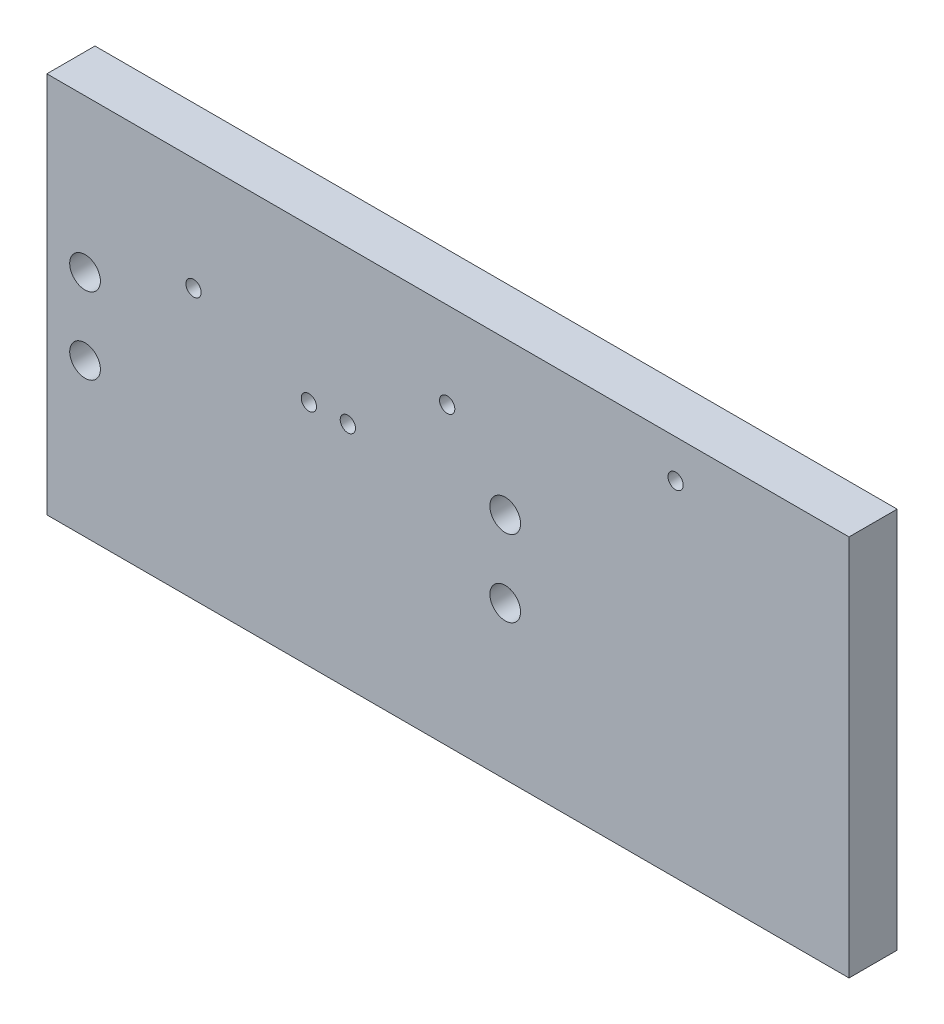
SolidWorks part; units mm, degrees
ref_plane "Front Plane" through (0, 0, 0) normal (0, 0, 1) x (1, 0, 0)
ref_plane "Top Plane" through (0, 0, 0) normal (0, 1, 0) x (1, 0, 0)
ref_plane "Right Plane" through (0, 0, 0) normal (1, 0, 0) x (0, 0, -1)
ref_plane "Dielectric_Layer Layer 1" through (0, 0, 1.6) normal (0, 0, 1) x (1, 0, 0)
sketch "Sketch1" plane through (0, 0, 0) normal (0, 0, 1) x (1, 0, 0)
  line L0 (0, 0) -> (26.67, 0)
  line L1 (26.67, 0) -> (26.67, 12.7)
  line L2 (26.67, 12.7) -> (0, 12.7)
  line L3 (0, 12.7) -> (0, 0)
extrude "Board_Outline" add sketch "Sketch1" along normal blind 1.6 separate body
sketch "Sketch2" plane through (0, 0, 0) normal (0, 0, 1) x (1, 0, 0)
  circle A0 centre (8.7122, 7.5946) radius 0.254
  circle A1 centre (10.0076, 7.62) radius 0.254
  circle A2 centre (13.3096, 9.8298) radius 0.254
  circle A3 centre (20.9042, 11.43) radius 0.254
  circle A4 centre (4.8768, 8.9662) radius 0.254
extrude "NPTH" cut sketch "Sketch2" along normal through all
sketch "Sketch3" plane through (0, 0, 0) normal (0, 0, 1) x (1, 0, 0)
  circle A0 centre (1.27, 7.62) radius 0.51
  circle A1 centre (1.27, 5.08) radius 0.51
  circle A2 centre (15.24, 7.62) radius 0.51
  circle A3 centre (15.24, 5.08) radius 0.51
extrude "PTH" cut sketch "Sketch3" along normal through all
